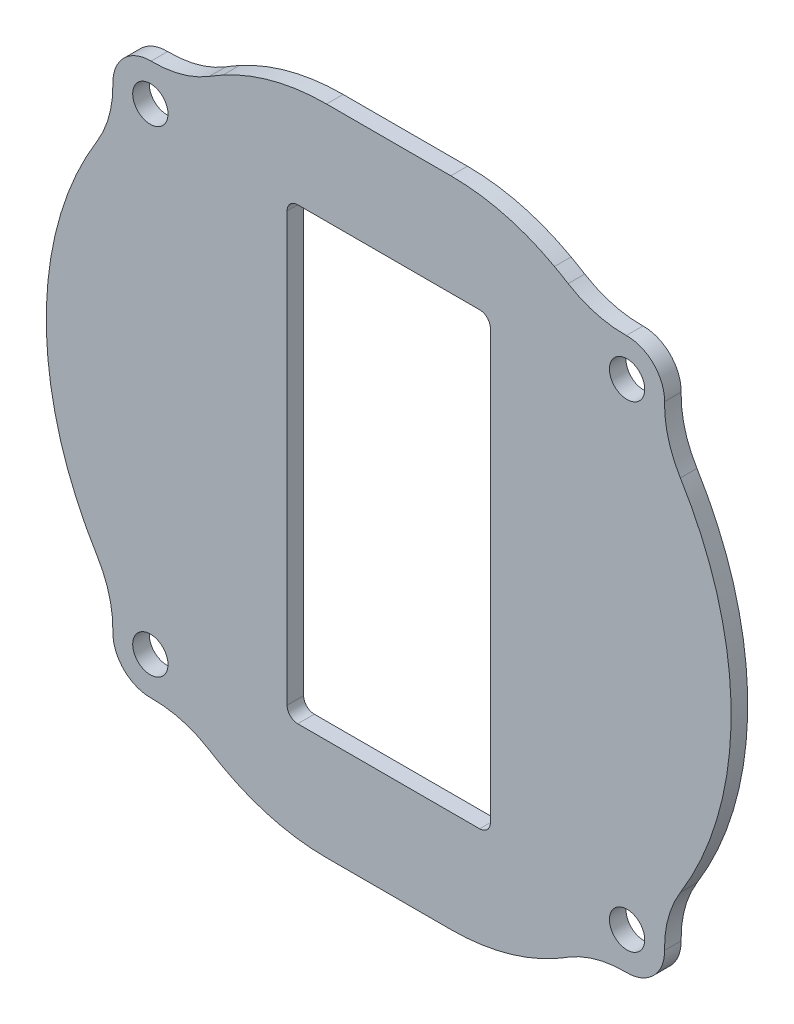
SolidWorks part; units mm, degrees
material "Epoxy, renforcé"
ref_plane "Plan de face" through (0, 0, 0) normal (0, 0, 1) x (1, 0, 0)
ref_plane "Plan de dessus" through (0, 0, 0) normal (0, 1, 0) x (1, 0, 0)
ref_plane "Plan de droite" through (0, 0, 0) normal (1, 0, 0) x (0, 0, -1)
sketch "Esquisse1" plane through (0, 0, 0) normal (0, 0, 1) x (1, 0, 0)
  line L0 (0, 31.5) -> (0, 0) construction
  line L1 (15.5, 21) -> (-15.5, 21) construction
  line L2 (15.5, 21) -> (15.5, -21) construction
  line L3 (15.5, -21) -> (-15.5, -21) construction
  line L4 (-15.5, 21) -> (-15.5, -21) construction
  line L5 (15.5, 21) -> (-15.5, -21) construction
  line L6 (15.5, -21) -> (-15.5, 21) construction
  line L7 (0, 0) -> (-22.2739, 22.2739) construction
  arc A0 (-24.9579, 20.0276) -> (-24.9579, -20.0276) centre (0, 0) ccw
  circle A1 centre (0, 0) radius 31.5 construction
  circle A2 centre (-22.2739, 22.2739) radius 1.65
  circle A3 centre (22.2739, 22.2739) radius 1.65
  circle A4 centre (22.2739, -22.2739) radius 1.65
  circle A5 centre (-22.2739, -22.2739) radius 1.65
  arc A6 (-20.0276, 24.9579) -> (-24.9579, 20.0276) centre (-22.2739, 22.2739) ccw
  arc A7 (24.9579, 20.0276) -> (20.0276, 24.9579) centre (22.2739, 22.2739) ccw
  arc A8 (20.0276, -24.9579) -> (24.9579, -20.0276) centre (22.2739, -22.2739) ccw
  arc A9 (-24.9579, -20.0276) -> (-20.0276, -24.9579) centre (-22.2739, -22.2739) ccw
  arc A10 (20.0276, 24.9579) -> (-20.0276, 24.9579) centre (0, 0) ccw
  arc A11 (24.9579, -20.0276) -> (24.9579, 20.0276) centre (0, 0) ccw
  arc A13 (-20.0276, -24.9579) -> (20.0276, -24.9579) centre (0, 0) ccw
  point P0 (0, 0)
  point P21 (0, 0)
  point P29 (0, 0)
  dimension "D3" = 63
  dimension "D5" = 3.3
  dimension "D7" = 64
  dimension "D9" = 7
  dimension "D1" = 31
  dimension "D2" = 42
  dimension "D4" = 45
  dimension "D6" = 4
  dimension "D8" = 4
extrude "Boss.-Extru.1" add sketch "Esquisse1" along normal blind 1.55
sketch "Esquisse2" plane through (0, 0, 1.55) normal (0, 0, 1) x (1, 0, 0)
  line L1 (9.5, 21) -> (-9.5, 21)
  line L2 (9.5, 21) -> (9.5, -21)
  line L3 (9.5, -21) -> (-9.5, -21)
  line L4 (-9.5, 21) -> (-9.5, -21)
  line L5 (9.5, 21) -> (-9.5, -21) construction
  line L6 (9.5, -21) -> (-9.5, 21) construction
  point P0 (0, 0)
  dimension "D1" = 19
  dimension "D2" = 42
extrude "Enlèv. mat.-Extru.1" cut sketch "Esquisse2" against normal through all
fillet "Congé1" radius 10 8 edges at (24.9579, -20.0276, 0.775) (20.0276, -24.9579, 0.775) (-20.0276, -24.9579, 0.775) (-24.9579, -20.0276, 0.775) (-24.9579, 20.0276, 0.775) (-20.0276, 24.9579, 0.775) (20.0276, 24.9579, 0.775) (24.9579, 20.0276, 0.775)
fillet "Congé2" radius 1 4 edges at (9.5, 21, 0.775) (9.5, -21, 0.775) (-9.5, -21, 0.775) (-9.5, 21, 0.775)
sketch "Esquisse3" plane through (0, 0, 1.55) normal (0, 0, 1) x (1, 0, 0)
  line L1 (35, -30.5) -> (-35, -30.5)
  line L2 (35, -30.5) -> (35, 30.5)
  line L3 (35, 30.5) -> (-35, 30.5)
  line L4 (-35, -30.5) -> (-35, 30.5)
  line L5 (35, -30.5) -> (-35, 30.5) construction
  line L6 (35, 30.5) -> (-35, -30.5) construction
  point P0 (0, 0)
  dimension "D1" = 61
  dimension "D2" = 70
extrude "Enlèv. mat.-Extru.2" cut sketch "Esquisse3" against normal through all flip side to cut
fillet "Congé3" radius 20 4 edges at (-9.6825, -30.5, 0.775) (9.6825, -30.5, 0.775) (9.6825, 30.5, 0.775) (-9.6825, 30.5, 0.775)
